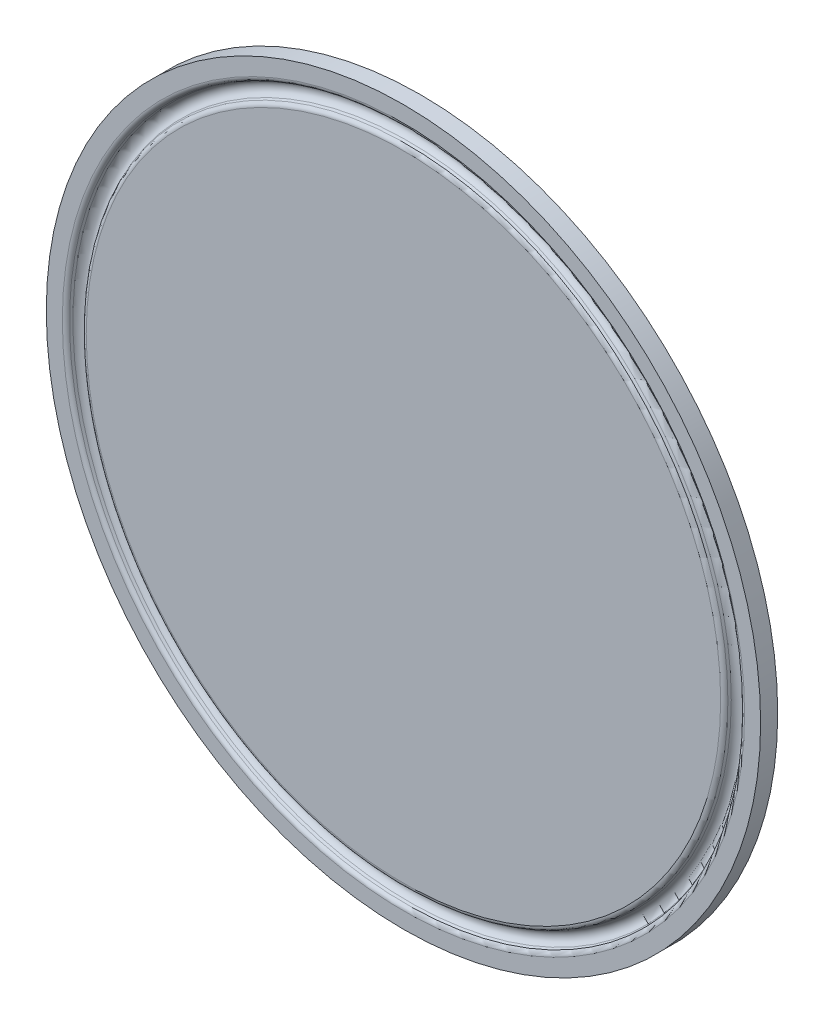
SolidWorks part; units mm, degrees
ref_plane "Front Plane" through (0, 0, 0) normal (0, 0, 1) x (1, 0, 0)
ref_plane "Top Plane" through (0, 0, 0) normal (0, 1, 0) x (1, 0, 0)
ref_plane "Right Plane" through (0, 0, 0) normal (1, 0, 0) x (0, 0, -1)
sketch "Sketch1" plane through (0, 0, 0) normal (1, 0, 0) x (0, 0, -1)
  line L0 (0, 0) -> (7.9248, 0) construction
  line L1 (0, 0) -> (0, 52.8099)
  line L2 (0, 59.4614) -> (2.8448, 59.4614)
  line L3 (2.8448, 59.4614) -> (7.9248, 45.5042)
  line L4 (7.9248, 45.5042) -> (7.9248, 0)
  line L5 (0, 56.7911) -> (0, 59.4614)
  line L6 (0.4797, 56.0663) -> (0.8729, 55.8994)
  line L7 (0.4797, 53.5347) -> (0.8729, 53.7016)
  line L8 (0, 56.2699) -> (0, 53.3311) construction
  line L9 (0, 54.8005) -> (0.4064, 54.8005) construction
  line L10 (0, 0) -> (7.9248, 0)
  arc A0 (0.8729, 53.7016) -> (0.8729, 55.8994) centre (0.4064, 54.8005) ccw
  arc A2 (0, 52.8099) -> (0.4797, 53.5347) centre (0.7874, 52.8099) cw
  arc A3 (0, 56.7911) -> (0.4797, 56.0663) centre (0.7874, 56.7911) ccw
  dimension "K" = 1.1938
  dimension "L" = 0.7874
  dimension "I" = 20
  dimension "C" = 91.0084
  dimension "F" = 2.8448
  dimension "H" = 0.4064
  dimension "B" = 109.601
  dimension "A" = 118.9228
  dimension "M" = 46
  dimension "N" = 23
  dimension "Length" = 7.9248
revolve "Revolve1" add sketch "Sketch1" angle 360 about L0
